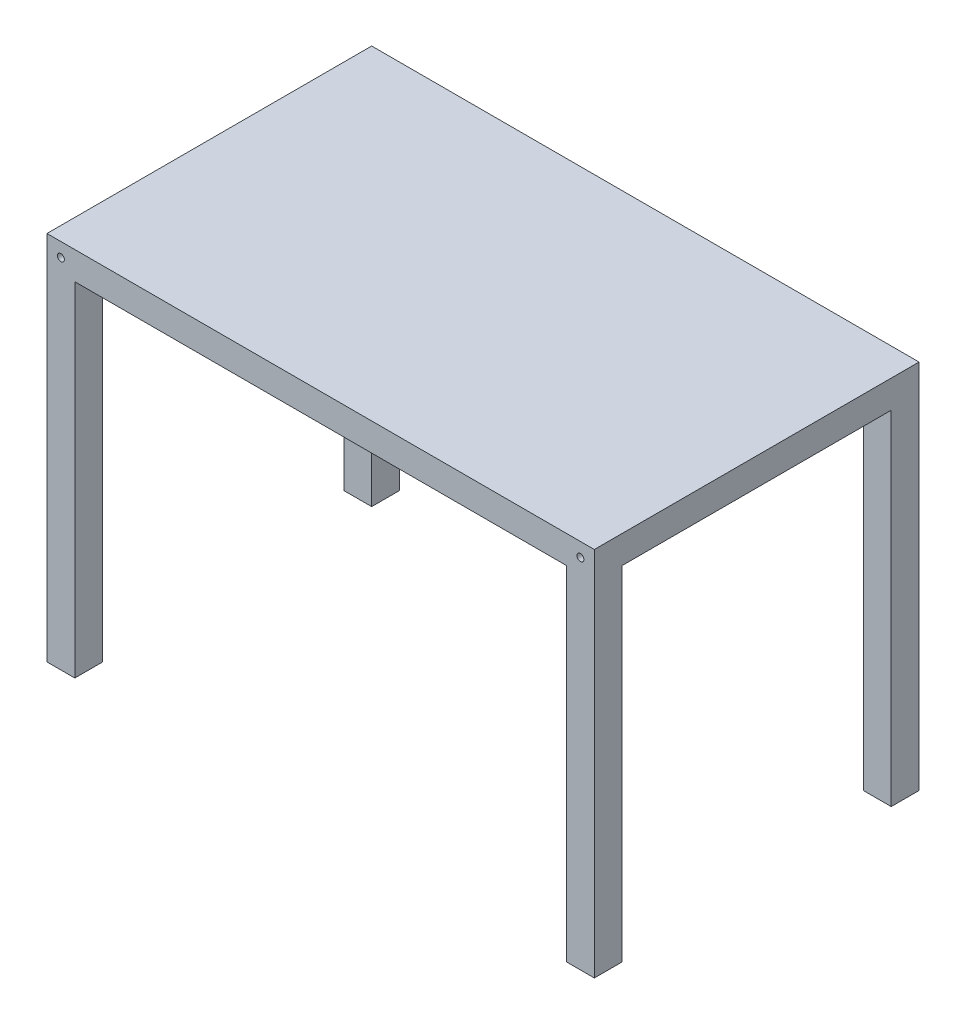
SolidWorks part; units mm, degrees
material "Acier non allié"
ref_plane "Plan de face" through (0, 0, 0) normal (0, 0, 1) x (1, 0, 0)
ref_plane "Plan de dessus" through (0, 0, 0) normal (0, 1, 0) x (1, 0, 0)
ref_plane "Plan de droite" through (0, 0, 0) normal (1, 0, 0) x (0, 0, -1)
sketch "Esquisse1" plane through (0, 0, 0) normal (0, 0, 1) x (1, 0, 0)
  line L0 (0, 0) -> (0, 800)
  line L1 (0, 800) -> (1180, 800)
  line L2 (1180, 800) -> (1180, 0)
  line L3 (1180, 0) -> (0, 0)
  dimension "D1" = 800
  dimension "D2" = 1180
extrude "Boss.-Extru.1" add sketch "Esquisse1" along normal blind 700
sketch "Esquisse2" plane through (0, 0, 700) normal (0, 0, 1) x (1, 0, 0)
  line L0 (60, 0) -> (60, 740)
  line L1 (0, 0) -> (1180, 0) construction
  line L2 (60, 740) -> (1120, 740)
  line L3 (1120, 740) -> (1120, 0)
  line L4 (0, 800) -> (0, 0) construction
  line L5 (1180, 0) -> (1180, 800) construction
  line L6 (1180, 800) -> (0, 800) construction
  line L7 (60, 0) -> (1120, 0)
  dimension "D1" = 60
  dimension "D2" = 60
  dimension "D3" = 60
extrude "Enlèv. mat.-Extru.1" cut sketch "Esquisse2" against normal blind 700
sketch "Esquisse3" plane through (0, 0, 0) normal (-1, 0, 0) x (0, 0, 1)
  line L0 (60, 0) -> (60, 740)
  line L1 (700, 0) -> (0, 0) construction
  line L2 (60, 740) -> (640, 740)
  line L3 (640, 740) -> (640, 0)
  line L4 (640, 0) -> (60, 0)
  line L5 (0, 800) -> (0, 0) construction
  line L6 (700, 800) -> (700, 0) construction
  line L7 (700, 800) -> (0, 800) construction
  dimension "D1" = 60
  dimension "D2" = 60
  dimension "D3" = 60
sketch "Esquisse4" plane through (0, 0, 0) normal (-1, 0, 0) x (0, 0, 1)
extrude "Enlèv. mat.-Extru.2" cut sketch "Esquisse3" against normal blind 1240 contours L2 L3 L4 L0
sketch "Esquisse7" plane through (0, 0, 700) normal (0, 0, 1) x (1, 0, 0)
  line L0 (1120, 740) -> (60, 740) construction
  line L1 (0, 800) -> (0, 0) construction
  line L2 (1180, 0) -> (1180, 800) construction
  circle A0 centre (30, 770) radius 7.5
  circle A1 centre (1150, 770) radius 7.5
  dimension "D1" = 15
  dimension "D2" = 30
  dimension "D4" = 15
  dimension "D5" = 30
  dimension "D3" = 30
  dimension "D6" = 30
extrude "Enlèv. mat.-Extru.5" cut sketch "Esquisse7" against normal blind 50
